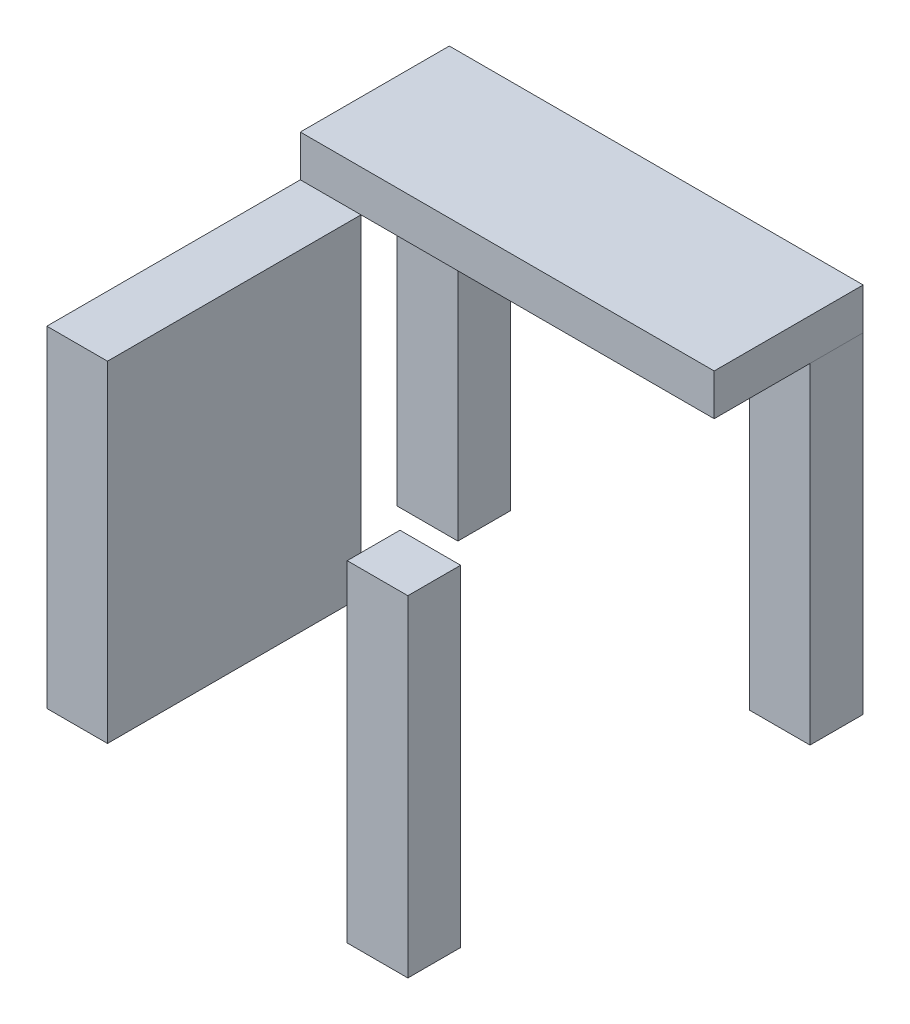
SolidWorks part; units mm, degrees
ref_plane "Front Plane" through (0, 0, 0) normal (0, 0, 1) x (1, 0, 0)
ref_plane "Top Plane" through (0, 0, 0) normal (0, 1, 0) x (1, 0, 0)
ref_plane "Right Plane" through (0, 0, 0) normal (1, 0, 0) x (0, 0, -1)
sketch "Sketch1" plane through (0, 0, 0) normal (0, 0, 1) x (1, 0, 0)
  line L1 (0, 0) -> (100, 0)
  line L2 (0, 0) -> (0, 10)
  line L3 (0, 10) -> (100, 10)
  line L4 (100, 0) -> (100, 10)
  dimension "D1" = 10
  dimension "D2" = 100
extrude "Boss-Extrude1" add sketch "Sketch1" along normal blind 36
sketch "Sketch2" plane through (0, 0, 0) normal (0, -1, 0) x (1, 0, 0)
  line L0 (85.3618, 110.0347) -> (100.0191, 110.0347)
  line L1 (0, 36) -> (14.6573, 36)
  line L2 (0, 36) -> (0, 97.2496)
  line L3 (0, 97.2496) -> (14.6573, 97.2496)
  line L4 (14.6573, 36) -> (14.6573, 97.2496)
  line L5 (85.3618, 110.0347) -> (85.3618, 97.2843)
  line L6 (85.3618, 97.2843) -> (100.0191, 97.2843)
  line L7 (100.0191, 110.0347) -> (100.0191, 97.2843)
  line L8 (-0.0191, 12.5688) -> (14.6382, 12.5688)
  line L9 (-0.0191, 12.5688) -> (-0.0191, -0.1816)
  line L10 (-0.0191, -0.1816) -> (14.6382, -0.1816)
  line L11 (14.6382, 12.5688) -> (14.6382, -0.1816)
  line L12 (85.2149, 12.7157) -> (99.8722, 12.7157)
  line L13 (85.2149, 12.7157) -> (85.2149, -0.0347)
  line L14 (85.2149, -0.0347) -> (99.8722, -0.0347)
  line L15 (99.8722, 12.7157) -> (99.8722, -0.0347)
extrude "Boss-Extrude2" add sketch "Sketch2" along normal blind 80
equation "\"LTest\" = 36mm"
equation "\"D1@Boss-Extrude1\"=\"LTest\""
